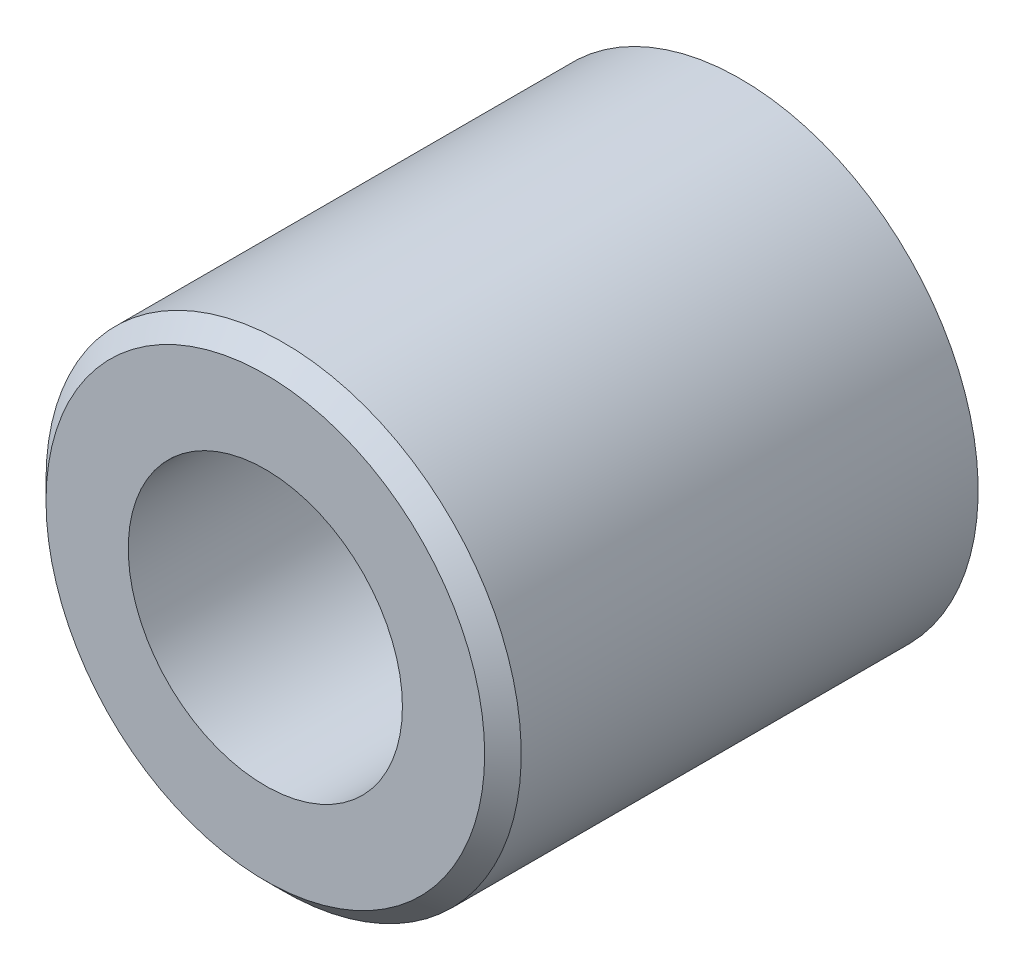
SolidWorks part; units mm, degrees
ref_plane "Спереди" through (0, 0, 0) normal (0, 0, 1) x (1, 0, 0)
ref_plane "Сверху" through (0, 0, 0) normal (0, 1, 0) x (1, 0, 0)
ref_plane "Справа" through (0, 0, 0) normal (1, 0, 0) x (0, 0, -1)
sketch "Эскиз1" plane through (0, 0, 0) normal (0, 0, 1) x (1, 0, 0)
  circle A0 centre (0, 0) radius 6.5
  dimension "D1" = 13
extrude "Основание-Вытянуть" add sketch "Эскиз1" along normal blind 13
sketch "Эскиз2" plane through (0, 0, 13) normal (0, 0, 1) x (1, 0, 0)
  circle A0 centre (0, 0) radius 3
  dimension "D1" = 6
extrude "Вырез-Вытянуть1" cut sketch "Эскиз2" against normal through all
sketch "Эскиз3" plane through (0, 0, 13) normal (0, 0, 1) x (1, 0, 0)
  circle A0 centre (0, 0) radius 3.75
  dimension "D1" = 7.5
extrude "Вырез-Вытянуть2" cut sketch "Эскиз3" against normal blind 8
chamfer "Фаска1" distance 0.5 angle 45
